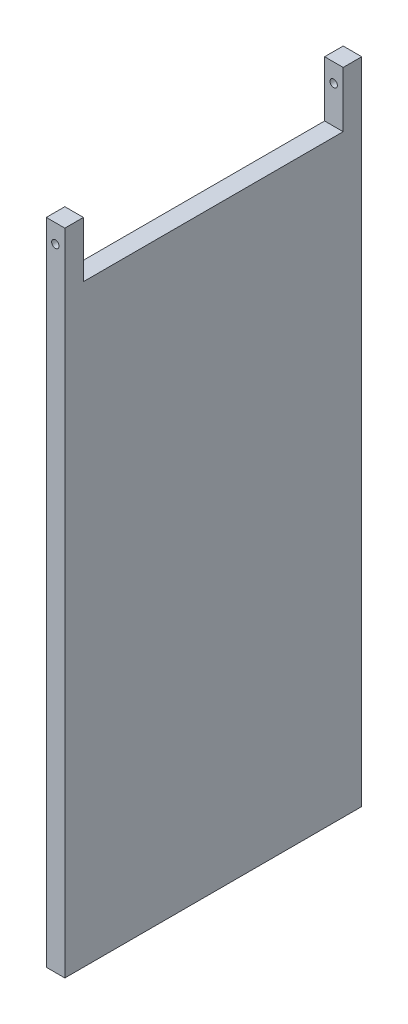
SolidWorks part; units mm, degrees
ref_plane "Plan de face" through (0, 0, 0) normal (0, 0, 1) x (1, 0, 0)
ref_plane "Plan de dessus" through (0, 0, 0) normal (0, 1, 0) x (1, 0, 0)
ref_plane "Plan de droite" through (0, 0, 0) normal (1, 0, 0) x (0, 0, -1)
sketch "Esquisse1" plane through (0, 0, 0) normal (0, 0, 1) x (1, 0, 0)
  line L1 (-7.4015, 128.8805) -> (-2.4015, 128.8805)
  line L2 (-7.4015, 128.8805) -> (-7.4015, -46.1195)
  line L3 (-7.4015, -46.1195) -> (-2.4015, -46.1195)
  line L4 (-2.4015, 128.8805) -> (-2.4015, -46.1195)
  circle A0 centre (-4.9564, 123.8805) radius 1
  dimension "D2" = 2
  dimension "D1" = 5
  dimension "D3" = 5
  dimension "D4" = 170
extrude "Boss.-Extru.1" add sketch "Esquisse1" along normal blind 80
sketch "Esquisse2" plane through (0, 0, 0) normal (1, 0, 0) x (0, 0, -1)
  line L0 (-80, 128.8805) -> (0, 128.8805) construction
  line L1 (-75, 128.8805) -> (-5, 128.8805)
  line L2 (-75, 128.8805) -> (-75, 113.8805)
  line L3 (-75, 113.8805) -> (-5, 113.8805)
  line L4 (-5, 128.8805) -> (-5, 113.8805)
  line L5 (-80, -46.1195) -> (-80, 128.8805) construction
  dimension "D1" = 70
  dimension "D2" = 15
  dimension "D3" = 0
  dimension "D4" = 5
extrude "Enlèv. mat.-Extru.1" cut sketch "Esquisse2" against normal blind 20
